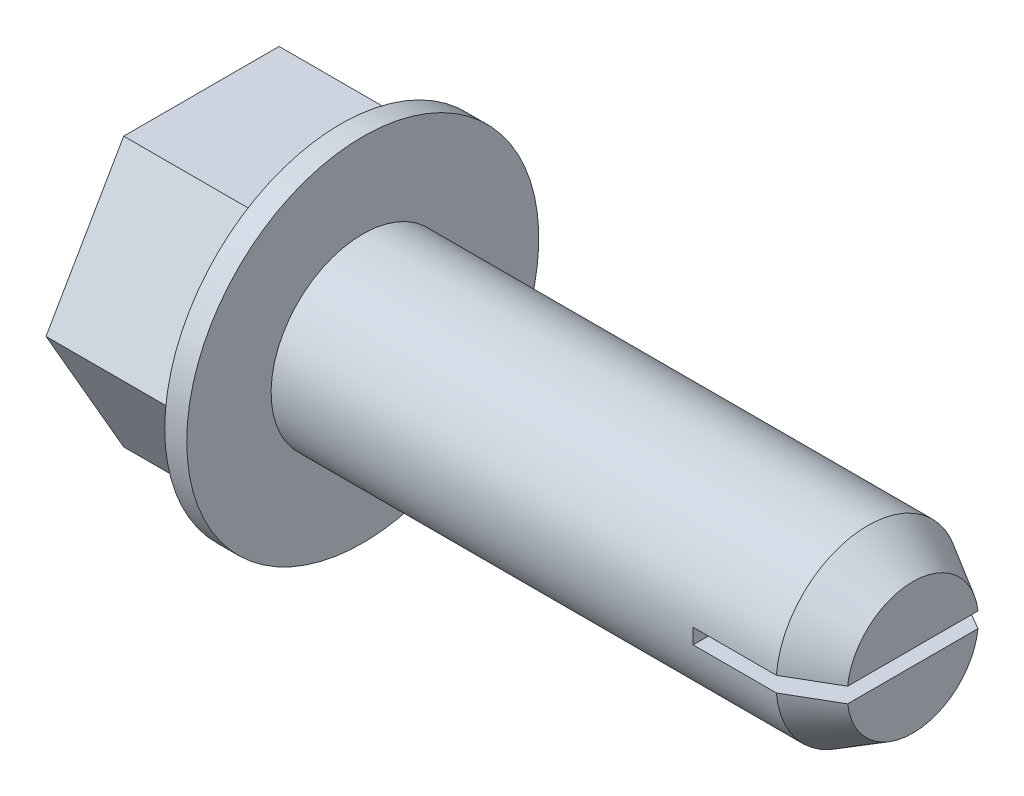
SolidWorks part; units mm, degrees
ref_plane "Front Plane" through (0, 0, 0) normal (0, 0, 1) x (1, 0, 0)
ref_plane "Top Plane" through (0, 0, 0) normal (0, 1, 0) x (1, 0, 0)
ref_plane "Right Plane" through (0, 0, 0) normal (1, 0, 0) x (0, 0, -1)
ref_plane "Plane1" through (0, 0, 0) normal (0, 0, -1) x (-1, 0, 0)
sketch "Sketch1" plane through (0, 0, 0) normal (0, 0, -1) x (-1, 0, 0)
  line L0 (0, 6.096) -> (0, 0)
  line L1 (0, 0) -> (0.762, 0)
  line L2 (0.762, 0) -> (0.762, 6.096)
  line L3 (0.762, 6.096) -> (0, 6.096)
  line L4 (0, 0) -> (0.762, 0) construction
revolve "Revolve1" add sketch "Sketch1" angle 360 about L4
sketch "Sketch2" plane through (0, 0, 0) normal (1, 0, 0) x (0, 0, -1)
  circle A0 centre (0, 0) radius 3.175
extrude "Boss-Extrude1" add sketch "Sketch2" along normal blind 19.05
sketch "Sketch3" plane through (19.05, 0, 0) normal (1, 0, 0) x (0, 0, -1)
  line L0 (3.164, 0.2646) -> (-3.164, 0.2646)
  arc A0 (-3.164, 0.2646) -> (3.164, 0.2646) centre (0, 0) ccw
extrude "Cut-Extrude1" cut sketch "Sketch3" against normal blind 4.445
sketch "Sketch4" plane through (14.605, 0, 0) normal (1, 0, 0) x (0, 0, -1)
  line L0 (-3.164, -0.2646) -> (3.164, -0.2646)
  arc A0 (3.164, -0.2646) -> (-3.164, -0.2646) centre (0, 0) cw
extrude "Boss-Extrude2" add sketch "Sketch4" along normal blind 4.445
sketch "Sketch5" plane through (-0.762, 0, 0) normal (-1, 0, 0) x (0, 0, 1)
  line L0 (-5.3819, 0) -> (-2.691, 4.6609)
  line L1 (-2.691, 4.6609) -> (2.691, 4.6609)
  line L2 (2.691, 4.6609) -> (5.3819, 0)
  line L3 (5.3819, 0) -> (2.691, -4.6609)
  line L4 (2.691, -4.6609) -> (-2.691, -4.6609)
  line L5 (-2.691, -4.6609) -> (-5.3819, 0)
extrude "Boss-Extrude3" add sketch "Sketch5" along normal blind 4.826
hole_wizard "M6.5 Clearance Hole1" positions "Sketch7" profile "Sketch6" hole size "M6.5" standard "ANSI Metric"
sketch "Sketch7" plane through (-5.588, 0, 0) normal (-1, 0, 0) x (0, 0, 1)
  point P0 (0, 0)
sketch "Sketch6" plane through (-5.588, 0, 0) normal (0, 1, 0) x (0, 0, 1)
  line L0 (0, 0) -> (0, 0.9652)
  line L1 (0, 0.9652) -> (3.7287, 0.9652)
  line L2 (3.7287, 0.9652) -> (3.7287, 0)
  line L5 (3.7287, 0) -> (0, 0)
  line L10 (0, 0.9652) -> (-3.7287, 0.9652) construction
  line L11 (0, -6.35) -> (0, 107.95) construction
  dimension "Hole Dia." = 7.4574
  dimension "Hole Depth" = 0.9652
  dimension "Drill Angle" = 180
chamfer "Chamfer1" distance 0.9017 angle 60 2 edges at (19.05, -3.175, 0) (19.05, 3.175, 0)
